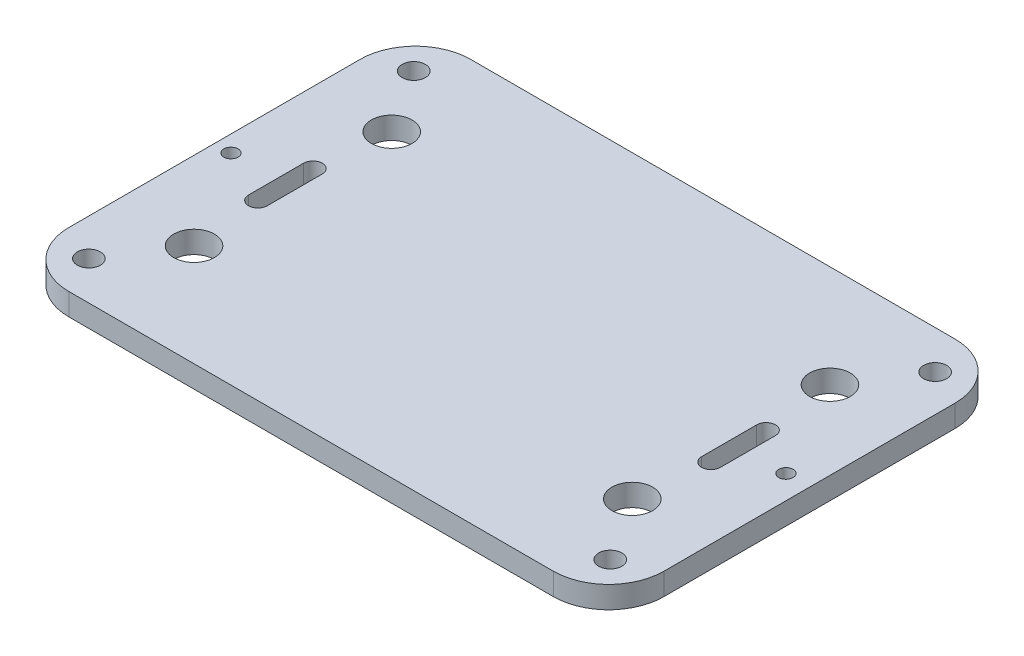
SolidWorks part; units mm, degrees
ref_plane "Piano frontale" through (0, 0, 0) normal (0, 0, 1) x (1, 0, 0)
ref_plane "Piano superiore" through (0, 0, 0) normal (0, 1, 0) x (1, 0, 0)
ref_plane "Piano destro" through (0, 0, 0) normal (1, 0, 0) x (0, 0, -1)
sketch "Schizzo1" plane through (0, 0, 0) normal (0, 1, 0) x (1, 0, 0)
  line L0 (-6.7, 66) -> (-6.7, 7) construction
  line L1 (-10.05, 0) -> (-98.05, 0)
  line L2 (0, 10.05) -> (0, 62.95)
  line L3 (-10.05, 73) -> (-98.05, 73)
  line L4 (-108.1, 10.05) -> (-108.1, 62.95)
  line L5 (-6.7, 66) -> (-101.4, 66) construction
  line L6 (-101.4, 66) -> (-101.4, 7) construction
  line L7 (-101.4, 7) -> (-6.7, 7) construction
  line L8 (0, 36.5) -> (-108.1, 36.5) construction
  line L9 (-54.05, 0) -> (-54.05, 73) construction
  line L10 (-93.85, 54.45) -> (-14.25, 54.45) construction
  line L11 (-14.25, 54.45) -> (-14.25, 18.55) construction
  line L12 (-14.25, 18.55) -> (-93.85, 18.55) construction
  line L13 (-93.85, 18.55) -> (-93.85, 54.45) construction
  line L14 (-95.2, 31.5) -> (-95.2, 41.5) construction
  line L15 (-96.9, 31.5) -> (-96.9, 41.5)
  line L16 (-93.5, 31.5) -> (-93.5, 41.5)
  line L17 (-12.9, 31.5) -> (-12.9, 41.5) construction
  line L18 (-14.6, 31.5) -> (-14.6, 41.5)
  line L19 (-11.2, 31.5) -> (-11.2, 41.5)
  line L20 (-8.8, 7) -> (-8.8, 66) construction
  line L21 (-99.3, 66) -> (-99.3, 7) construction
  circle A0 centre (-6.7, 66) radius 2.1
  circle A1 centre (-6.7, 7) radius 2.1
  circle A2 centre (-101.4, 66) radius 2.1
  circle A3 centre (-101.4, 7) radius 2.1
  arc A4 (-98.05, 0) -> (-108.1, 10.05) centre (-98.05, 10.05) cw
  arc A5 (0, 10.05) -> (-10.05, 0) centre (-10.05, 10.05) cw
  arc A6 (0, 62.95) -> (-10.05, 73) centre (-10.05, 62.95) ccw
  arc A7 (-98.05, 73) -> (-108.1, 62.95) centre (-98.05, 62.95) ccw
  circle A8 centre (-93.85, 54.45) radius 3.7
  circle A9 centre (-93.85, 18.55) radius 3.7
  circle A10 centre (-14.25, 18.55) radius 3.7
  circle A11 centre (-14.25, 54.45) radius 3.7
  arc A12 (-96.9, 31.5) -> (-93.5, 31.5) centre (-95.2, 31.5) ccw
  arc A13 (-93.5, 41.5) -> (-96.9, 41.5) centre (-95.2, 41.5) ccw
  arc A14 (-14.6, 31.5) -> (-11.2, 31.5) centre (-12.9, 31.5) ccw
  arc A15 (-11.2, 41.5) -> (-14.6, 41.5) centre (-12.9, 41.5) ccw
  circle A16 centre (-4.3, 36.5) radius 1.3
  circle A17 centre (-105.1, 36.5) radius 1.3
  point P13 (-6.7, 36.5)
  point P18 (-54.05, 66)
  point P19 (-98.05, 73)
  point P20 (-10.05, 73)
  point P23 (-108.1, 0)
  point P26 (0, 0)
  point P31 (-108.1, 73)
  point P40 (-93.85, 36.5)
  point P41 (-54.05, 18.55)
  point P44 (-95.2, 36.5)
  point P49 (-12.9, 36.5)
  point P64 (-11.2413, 36.5)
  dimension "D3" = 4.2
  dimension "D4" = 94.7
  dimension "D8" = 10.05
  dimension "D9" = 7.4
  dimension "D13" = 10
  dimension "D14" = 2.6
  dimension "D15" = 6.9
  dimension "D16" = 8.2
  dimension "D1" = 108.1
  dimension "D2" = 73
  dimension "D5" = 59
  dimension "D6" = 88
  dimension "D7" = 44
  dimension "D10" = 35.9
  dimension "D11" = 79.6
  dimension "D12" = 3.4
  dimension "D17" = 11.2
  dimension "D18" = 11.2
extrude "Estrusione-Estrusione1" add sketch "Schizzo1" along normal blind 4
